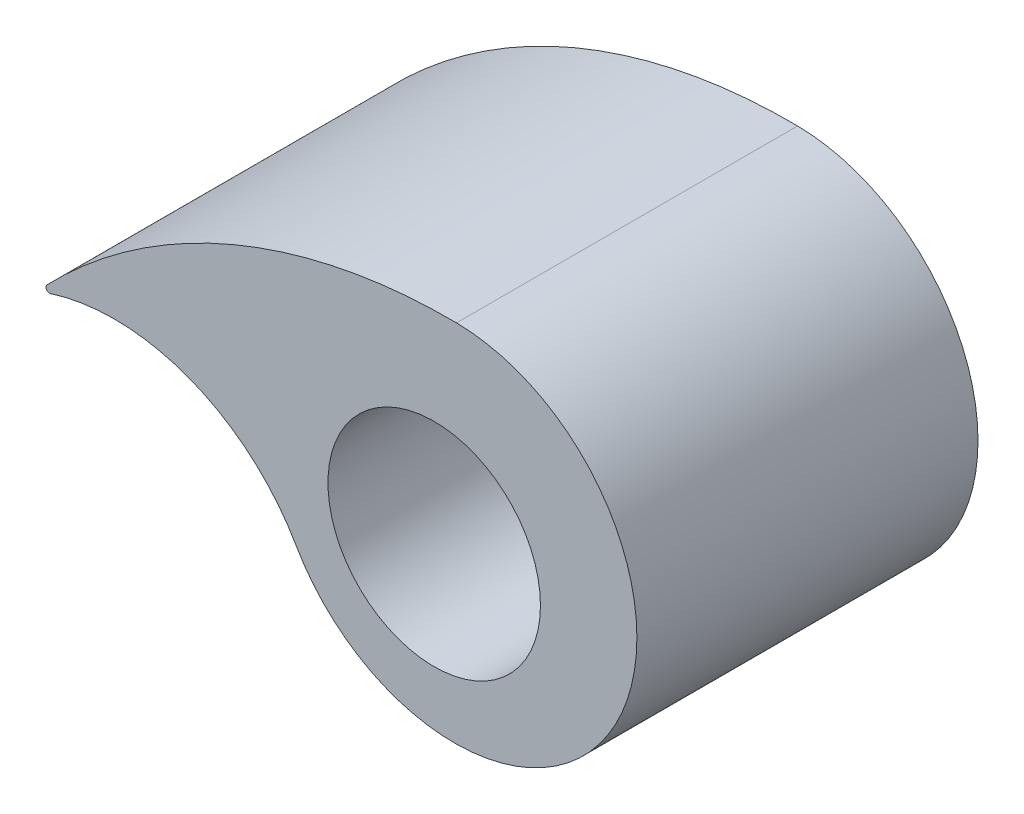
SolidWorks part; units mm, degrees
material "Malleable Cast Iron"
ref_plane "Front Plane" through (0, 0, 0) normal (0, 0, 1) x (1, 0, 0)
ref_plane "Top Plane" through (0, 0, 0) normal (0, 1, 0) x (1, 0, 0)
ref_plane "Right Plane" through (0, 0, 0) normal (1, 0, 0) x (0, 0, -1)
sketch "Base Sketch" plane through (0, 0, 0) normal (0, 0, 1) x (1, 0, 0)
  line L0 (29.8564, 0) -> (20.6287, -9.2277) construction
  line L1 (0, 0) -> (42.9064, 0) construction
  arc A0 (30, 13.0492) -> (0.7062, 0.7548) centre (29.5599, -26.9484) ccw
  arc A1 (18.534, -6.4889) -> (30, 13.0492) centre (29.8564, 0) ccw
  arc A2 (18.534, -6.4889) -> (0.9625, 0.3435) centre (5.5198, -13.9475) ccw
  arc A3 (0.9625, 0.3435) -> (0.7062, 0.7548) centre (0.8865, 0.5816) cw
  circle A4 centre (28.4068, -1.4496) radius 7.6
  dimension "D1" = 80
  dimension "D2" = 26.1
  dimension "D3" = 0.25
  dimension "D5" = 15
  dimension "D6" = 15.2
  dimension "D8" = 11
  dimension "D4" = 30
  dimension "D7" = 45
extrude "Base" add sketch "Base Sketch" against normal blind 24.4
